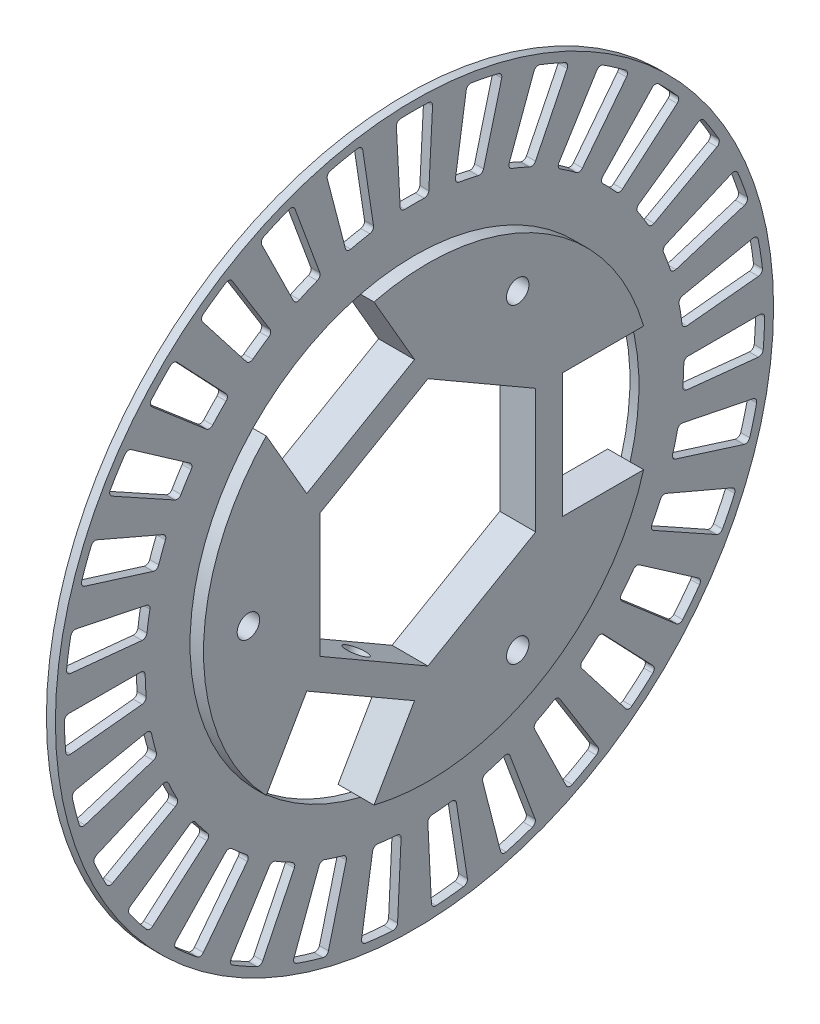
SolidWorks part; units mm, degrees
ref_plane "Front Plane" through (0, 0, 0) normal (0, 0, 1) x (1, 0, 0)
ref_plane "Top Plane" through (0, 0, 0) normal (0, 1, 0) x (1, 0, 0)
ref_plane "Right Plane" through (0, 0, 0) normal (1, 0, 0) x (0, 0, -1)
sketch "Sketch3" plane through (0, 0, 0) normal (0, 0, 1) x (1, 0, 0)
  line L0 (0, 0) -> (0, 5.9873) construction
  line L1 (-2, 0) -> (2, 0)
  line L2 (2, 0) -> (2, 25)
  line L3 (2, 25) -> (0.5, 25)
  line L4 (0.5, 25) -> (0.5, 40)
  line L5 (0.5, 40) -> (-0.5, 40)
  line L6 (0, 40) -> (0, 0) construction
  line L7 (-2, 25) -> (-0.5, 25)
  line L8 (-2, 0) -> (-2, 25)
  line L9 (-0.5, 25) -> (-0.5, 40)
  dimension "D1" = 2
  dimension "D2" = 0.5
  dimension "D3" = 25
  dimension "D4" = 40
revolve "Revolve1" add sketch "Sketch3" angle 360 about L1
sketch "Sketch4" plane through (2, 0, 0) normal (1, 0, 0) x (0, 0, -1)
  line L1 (0, 13.8564) -> (-12, 6.9282)
  line L2 (-12, 6.9282) -> (-12, -6.9282)
  line L3 (-12, -6.9282) -> (0, -13.8564)
  line L4 (0, -13.8564) -> (12, -6.9282)
  line L5 (12, -6.9282) -> (12, 6.9282)
  line L6 (12, 6.9282) -> (0, 13.8564)
  circle A1 centre (0, 0) radius 12 construction
  dimension "D1" = 24
extrude "Cut-Extrude1" cut sketch "Sketch4" against normal through all
sketch "Sketch9" plane through (2, 0, 0) normal (1, 0, 0) x (0, 0, -1)
  line L0 (0, 0) -> (-50.7581, 0) construction
  line L1 (-20, 0) -> (0, 0) construction
  line L3 (-1.5, -16.4545) -> (-13.5, -9.5263)
  line L7 (-12, -6.9282) -> (0, -13.8564) construction
  line L8 (-13.5, -9.5263) -> (-18.0104, -17.3385)
  line L10 (-6.0104, -24.2667) -> (-1.5, -16.4545)
  circle A0 centre (-20, 0) radius 1.25
  arc A1 (-25, 0) -> (-6.0104, -24.2667) centre (0, 0) ccw
  circle A2 centre (0, 0) radius 25 construction
  circle M7 centre (0, 0) radius 25
  dimension "D1" = 2.5
  dimension "D2" = 3
  dimension "D3" = 20
extrude "Cut-Extrude3" cut sketch "Sketch9" against normal through all contours L10 L3 L8 M7 | A0
sketch "Sketch10" plane through (0.5, 0, 0) normal (1, 0, 0) x (0, 0, -1)
  line L0 (0, 0) -> (0, 48.2778) construction
  line L1 (0, 0) -> (2.0411, 38.9466)
  line L2 (0, 0) -> (-2.0411, 38.9466)
  circle A0 centre (0, 0) radius 39
  circle A1 centre (0, 0) radius 30
  dimension "D1" = 78
  dimension "D2" = 60
  dimension "D3" = 3
  dimension "D4" = 3
extrude "Cut-Extrude4" cut sketch "Sketch10" against normal through all contours A1 L0 A0 L2 | L0 A1 L1 A0
fillet "Fillet1" radius 0.5 4 edges at (0, 29.9589, -1.5701) (0, 29.9589, 1.5701) (0, 38.9466, 2.0411) (0, 38.9466, -2.0411)
pattern_circular "CirPattern4" count 31 over 360 about axis through (0, 0, 0) along (1, 0, 0) of "Fillet1", "Cut-Extrude4"
pattern_circular "CirPattern6" count 3 over 360 about axis through (0, 0, 0) along (1, 0, 0) of "Cut-Extrude3"
hole_wizard "M2 Clearance Hole1" positions "Sketch13" profile "Sketch12" hole size "M2" standard "ANSI Metric"
sketch "Sketch13" plane through (0, -12.9904, 7.5) normal (0, -0.866, 0.5) x (-1, 0, 0)
  line L0 (2, 6.9282) -> (2, -6.9282) construction
  line L1 (0, 0) -> (0, 6.9282) construction
  line L5 (0, 0) -> (0, -6.9282) construction
  line L11 (2, 6.9282) -> (-2, 6.9282) construction
  line L12 (2, -6.9282) -> (-2, -6.9282) construction
  point P0 (0, 0)
  dimension "D1" = 2
sketch "Sketch12" plane through (0, -12.9904, 7.5) normal (1, 0, 0) x (0, -0.5, -0.866)
  line L0 (0, 0) -> (0, 3)
  line L1 (0, 3) -> (1.2, 3)
  line L2 (1.2, 3) -> (1.2, 0)
  line L5 (1.2, 0) -> (0, 0)
  line L11 (0, -6.35) -> (0, 107.95) construction
  dimension "Thru Hole Dia." = 2.4
  dimension "Thru Hole Depth" = 3
